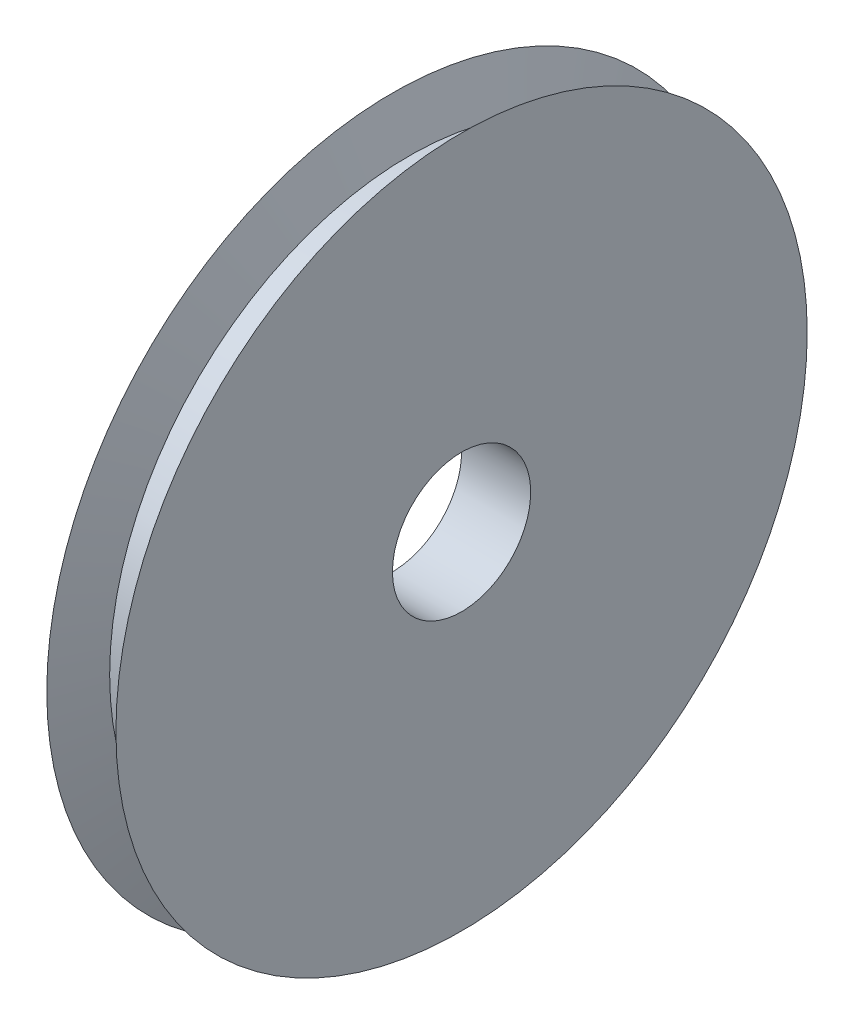
SolidWorks part; units mm, degrees
ref_plane "Alzado" through (0, 0, 0) normal (0, 0, 1) x (1, 0, 0)
ref_plane "Planta" through (0, 0, 0) normal (0, 1, 0) x (1, 0, 0)
ref_plane "Vista lateral" through (0, 0, 0) normal (1, 0, 0) x (0, 0, -1)
sketch "Croquis1" plane through (0, 0, 0) normal (0, 0, 1) x (1, 0, 0)
  line L0 (-41.4613, 0) -> (47.5084, 0) construction
  line L1 (0, 0) -> (0, 65) construction
  line L2 (7.5, 15) -> (-7.5, 15)
  line L3 (7.5, 15) -> (7.5, 75)
  line L5 (-7.5, 15) -> (-7.5, 75)
  line L6 (-7.5, 75) -> (-3.8603, 65)
  line L7 (-3.8603, 65) -> (3.8603, 65)
  line L8 (7.5, 75) -> (3.8603, 65)
  point P7 (0, 15)
  point P12 (-4.8052, 64.9198)
  point P13 (0, 65)
  point P14 (-5.6544, 64.9198)
  point P15 (-4.1624, 65)
  point P17 (-5.1537, 64.5582)
  dimension "D1" = 15
  dimension "D3" = 40
  dimension "D4" = 65
  dimension "D5" = 15
revolve "Revolución1" add sketch "Croquis1" angle 360 about L0
